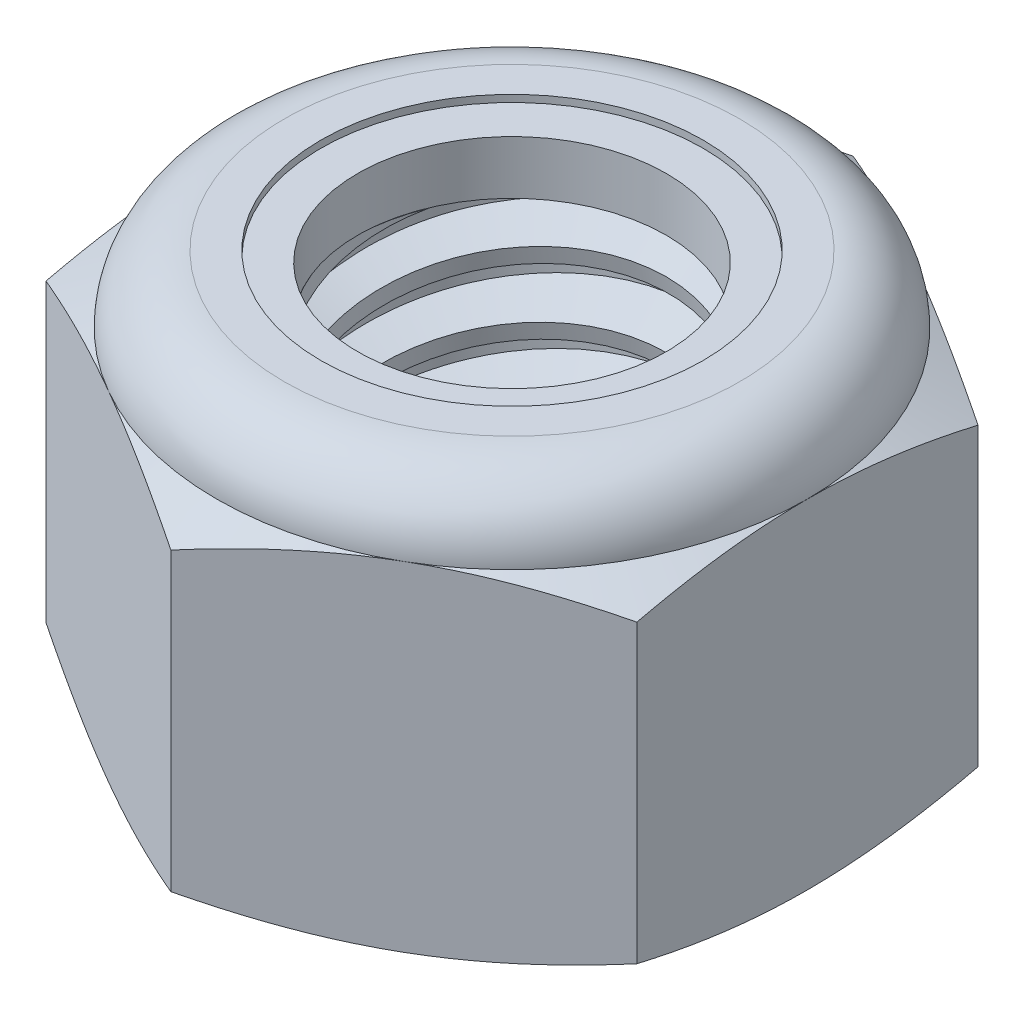
SolidWorks part; units mm, degrees
material "AISI 304"
ref_plane "Front" through (0, 0, 0) normal (0, 0, 1) x (1, 0, 0)
ref_plane "Top" through (0, 0, 0) normal (0, 1, 0) x (1, 0, 0)
ref_plane "Right" through (0, 0, 0) normal (1, 0, 0) x (0, 0, -1)
sketch "Sketch1" plane through (0, 0, 0) normal (0, 1, 0) x (1, 0, 0)
  line L1 (0, 7.3323) -> (-6.35, 3.6662)
  line L2 (-6.35, 3.6662) -> (-6.35, -3.6662)
  line L3 (-6.35, -3.6662) -> (0, -7.3323)
  line L4 (0, -7.3323) -> (6.35, -3.6662)
  line L5 (6.35, -3.6662) -> (6.35, 3.6662)
  line L6 (6.35, 3.6662) -> (0, 7.3323)
  circle A0 centre (0, 0) radius 6.35 construction
  dimension "Hex Flats" = 12.7
extrude "Extrude1" add sketch "Sketch1" along normal blind 8.7312
sketch "Sketch2" plane through (0, 0, 0) normal (1, 0, 0) x (0, 0, -1)
  line L0 (-3.9624, 0) -> (-3.9624, 8.7312) construction
  line L1 (0, 0) -> (3.9624, 0)
  line L2 (0, 0) -> (0, 8.7312)
  line L3 (0, 8.7312) -> (3.9624, 8.7312)
  line L4 (3.9624, 0) -> (3.9624, 8.7312)
  line L5 (-3.6662, 8.7312) -> (3.6662, 8.7312) construction
  line L7 (0, -3.9624) -> (0, 0) construction
  dimension "Thread Dia" = 7.9248
revolve "Revolve1" add sketch "Sketch2" angle 360 about L7
sketch "Sketch3" plane through (0, 0, 0) normal (1, 0, 0) x (0, 0, -1)
  line L0 (3.9624, 8.7312) -> (-3.9624, 8.7312) construction
  line L1 (-3.9624, 8.7312) -> (-3.9624, 7.3201) construction
  line L2 (-3.9624, 7.3201) -> (3.9624, 8.7312) construction
  line L3 (3.9624, 8.7312) -> (3.9933, 8.5576) construction
  line L4 (3.9933, 8.5576) -> (4.2098, 7.342)
  line L5 (4.2098, 7.342) -> (3.3805, 7.6422)
  line L6 (3.3805, 7.6422) -> (3.3187, 7.9896)
  line L7 (3.3187, 7.9896) -> (3.9933, 8.5576)
  line L8 (3.3496, 7.8159) -> (4.1015, 7.9498) construction
  line L9 (3.9624, 8.7312) -> (3.9624, 7.925) construction
  line L10 (3.9624, 7.925) -> (-3.9624, 6.5139) construction
  line L11 (-3.9624, 6.5139) -> (-3.9624, 7.3201) construction
  line L12 (-0.2692, 8.7312) -> (0.2692, 5.7077) construction
  line L13 (-3.9624, 0) -> (-3.9624, 8.7312) construction
  line L14 (0, 8.7312) -> (3.9624, 8.7312) construction
  line L15 (3.9624, 0) -> (3.9624, 8.7312) construction
  point P13 (0, 7.2195)
  dimension "D1" = 0.1764
  dimension "D2" = 0.3528
  dimension "Thread Pitch" = 1.4111
  dimension "D4" = 60
  dimension "D5" = 1.4111
revolve "Cut-Revolve1" cut sketch "Sketch3" angle 360 about L12
pattern_linear "LPattern1" count 6 spacing 1.4111 along (0, -1, 0) count 2 spacing 1.4111 along (0, 1, 0) of "Cut-Revolve1"
sketch "Sketch4" plane through (0, 0, 0) normal (1, 0, 0) x (0, 0, -1)
  line L0 (0, 8.7312) -> (3.9624, 8.7312)
  line L1 (3.9624, 8.7312) -> (3.3187, 8.4311)
  line L2 (3.3187, 8.4311) -> (3.3187, 0.3002)
  line L3 (3.3187, 0.3002) -> (3.9624, 0)
  line L4 (3.9624, 0) -> (0, 0)
  line L5 (0, 0) -> (0, 8.7312)
  line L6 (3.9624, 0) -> (3.9624, 8.7312) construction
  line L7 (0, 8.7312) -> (3.9624, 8.7312) construction
  line L8 (0, 0) -> (3.9624, 0) construction
  line L9 (0, 0) -> (0, 8.7312) construction
  line L10 (0, 8.7312) -> (0, 9.4415) construction
  dimension "D1" = 25
revolve "Cut-Revolve2" cut sketch "Sketch4" angle 360 about L10
combine bodies "Combine1" operation type subtract main body 112 bodies to subtract 111
sketch "Sketch5" plane through (0, 0, 0) normal (1, 0, 0) x (0, 0, -1)
  line L0 (0, 0) -> (6.35, 0)
  line L1 (6.35, 0) -> (7.3323, 0.4581)
  line L2 (7.3323, 0.4581) -> (7.3323, 6.818)
  line L3 (7.3323, 6.818) -> (6.35, 7.276)
  line L4 (4.8948, 8.7312) -> (4.8948, 10.0012)
  line L5 (4.8948, 10.0012) -> (8.6023, 10.0012)
  line L6 (8.6023, 10.0012) -> (8.6023, -1.27)
  line L7 (8.6023, -1.27) -> (0, -1.27)
  line L8 (0, -1.27) -> (0, 0)
  line L9 (6.35, 7.276) -> (6.35, 0) construction
  line L10 (0, 0) -> (3.9624, 0) construction
  line L13 (7.3323, 3.638) -> (8.6023, 3.638) construction
  line L14 (7.3323, 8.7312) -> (7.3323, 0) construction
  line L15 (0, 0) -> (0, 10.0012) construction
  line L20 (0, 10.0012) -> (4.8948, 10.0012) construction
  line L22 (0, 8.7312) -> (3.9624, 8.7312) construction
  arc A0 (6.35, 7.276) -> (4.8948, 8.7312) centre (4.8948, 7.276) ccw
  dimension "D1" = 25
  dimension "D2" = 1.27
  dimension "D3" = 8.7312
  dimension "D4" = 1.4552
revolve "Cut-Revolve3" cut sketch "Sketch5" angle 360 about L15
sketch "Sketch6" plane through (0, 0, 0) normal (1, 0, 0) x (0, 0, -1)
  line L0 (0, 7.276) -> (6.1976, 7.276)
  line L1 (4.8948, 8.5788) -> (4.1067, 8.5788)
  line L2 (0, 10.0012) -> (0, 7.276)
  line L3 (4.1067, 10.0012) -> (0, 10.0012)
  line L4 (0, 10.0012) -> (4.8948, 10.0012) construction
  line L5 (0, 0) -> (0, 10.0012) construction
  line L6 (0, 10.0012) -> (0, 44.323) construction
  line L7 (4.1067, 8.5788) -> (4.1067, 10.0012)
  line L8 (4.8948, 8.7312) -> (4.8948, 8.5788) construction
  line L9 (4.1067, 8.5788) -> (3.3187, 8.5788) construction
  line L10 (3.3187, 8.5788) -> (3.3187, 8.4311) construction
  arc A0 (6.1976, 7.276) -> (4.8948, 8.5788) centre (4.8948, 7.276) ccw
  arc A1 (6.35, 7.276) -> (4.8948, 8.7312) centre (4.8948, 7.276) ccw construction
  dimension "D1" = 0.1524
revolve "Cut-Revolve4" cut sketch "Sketch6" angle 360 about L6
sketch "Sketch7" plane through (0, 0, 0) normal (1, 0, 0) x (0, 0, -1)
  line L0 (3.3187, 7.3522) -> (6.119, 7.3522)
  line L1 (4.8948, 8.5027) -> (3.3187, 8.5027)
  line L2 (3.3187, 8.5027) -> (3.3187, 7.3522)
  line L3 (3.3187, 7.3522) -> (0, 7.3522) construction
  line L4 (0, 7.3522) -> (0, 8.5027) construction
  line L5 (0, 8.5027) -> (3.3187, 8.5027) construction
  line L6 (3.3187, 7.3522) -> (3.3187, 7.276) construction
  line L7 (0, 7.276) -> (6.1976, 7.276) construction
  line L8 (4.8948, 8.5027) -> (4.8948, 8.5788) construction
  arc A0 (6.119, 7.3522) -> (4.8948, 8.5027) centre (4.8948, 7.276) ccw
  arc A2 (6.1976, 7.276) -> (4.8948, 8.5788) centre (4.8948, 7.276) ccw construction
  dimension "D1" = 0.0762
revolve "Revolve2" add sketch "Sketch7" angle 360 about L4
equation "\"D1@Sketch3\"=\"Thread Pitch@Sketch3\"/8"
equation "\"D2@Sketch3\"=\"Thread Pitch@Sketch3\"/4"
equation "\"D5@Sketch3\"=\"Thread Pitch@Sketch3\""
equation "\"D4@LPattern1\"=\"Thread Pitch@Sketch3\""
equation "\"D3@LPattern1\"=\"Thread Pitch@Sketch3\""
equation "\"D1@LPattern1\"=\"Height@Extrude1\"/\"Thread Pitch@Sketch3\""
equation "\"D4@Sketch5\"=\"Height@Extrude1\"/6"
